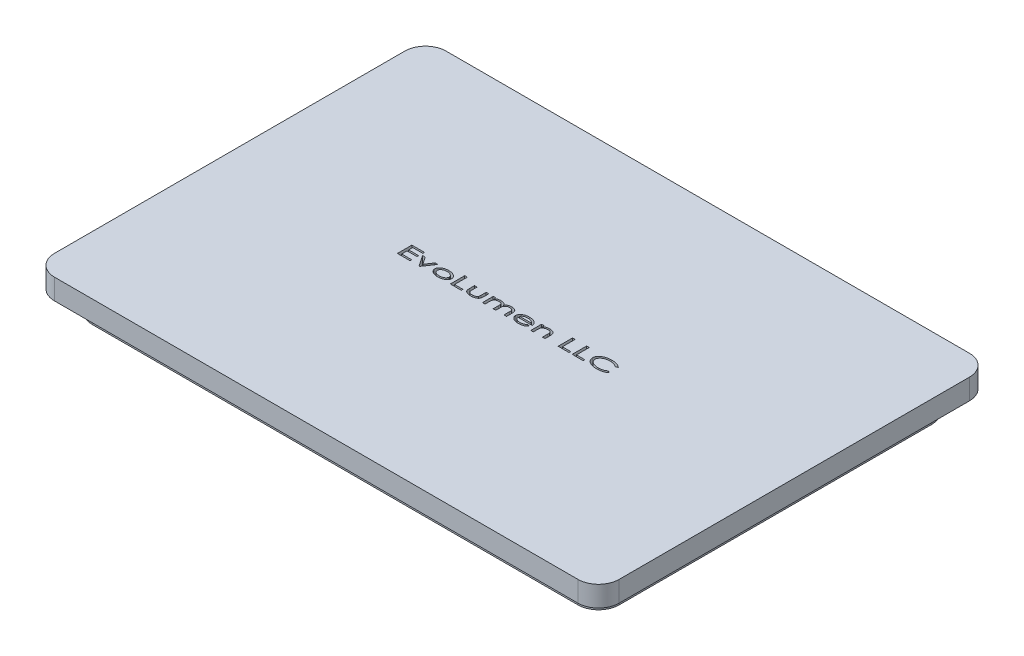
SolidWorks part; units mm, degrees
ref_plane "Front Plane" through (0, 0, 0) normal (0, 0, 1) x (1, 0, 0)
ref_plane "Top Plane" through (0, 0, 0) normal (0, 1, 0) x (1, 0, 0)
ref_plane "Right Plane" through (0, 0, 0) normal (1, 0, 0) x (0, 0, -1)
sketch "Sketch1" plane through (0, 0, 0) normal (0, 1, 0) x (1, 0, 0)
  line L1 (-63.875, -42.875) -> (63.875, -42.875)
  line L2 (-63.875, -42.875) -> (-63.875, 42.875)
  line L3 (-63.875, 42.875) -> (63.875, 42.875)
  line L4 (63.875, -42.875) -> (63.875, 42.875)
  line L5 (-63.875, -42.875) -> (63.875, 42.875) construction
  line L6 (-63.875, 42.875) -> (63.875, -42.875) construction
  point P0 (0, 0)
extrude "Boss-Extrude1" add sketch "Sketch1" along normal blind 5
fillet "Fillet1" radius 5 4 edges at (-63.875, 2.5, 42.875) (-63.875, 2.5, -42.875) (63.875, 2.5, -42.875) (63.875, 2.5, 42.875)
sketch "Sketch2" plane through (0, 5, 0) normal (0, 1, 0) x (1, 0, 0)
  line L1 (-68.5, -47.5) -> (68.5, -47.5)
  line L2 (-68.5, -47.5) -> (-68.5, 47.5)
  line L3 (-68.5, 47.5) -> (68.5, 47.5)
  line L4 (68.5, -47.5) -> (68.5, 47.5)
  line L5 (-68.5, -47.5) -> (68.5, 47.5) construction
  line L6 (-68.5, 47.5) -> (68.5, -47.5) construction
  point P0 (0, 0)
extrude "Boss-Extrude2" add sketch "Sketch2" along normal blind 5
fillet "Fillet2" radius 5 4 edges at (-68.5, 7.5, -47.5) (68.5, 7.5, -47.5) (68.5, 7.5, 47.5) (-68.5, 7.5, 47.5)
sketch "Sketch3" plane through (0, 10, 0) normal (0, 1, 0) x (1, 0, 0)
  text T0 "<b>EvoLumen LLC</b>" font "Century Gothic" height 3.5
extrude "Cut-Extrude2" cut sketch "Sketch3" against normal blind 2
